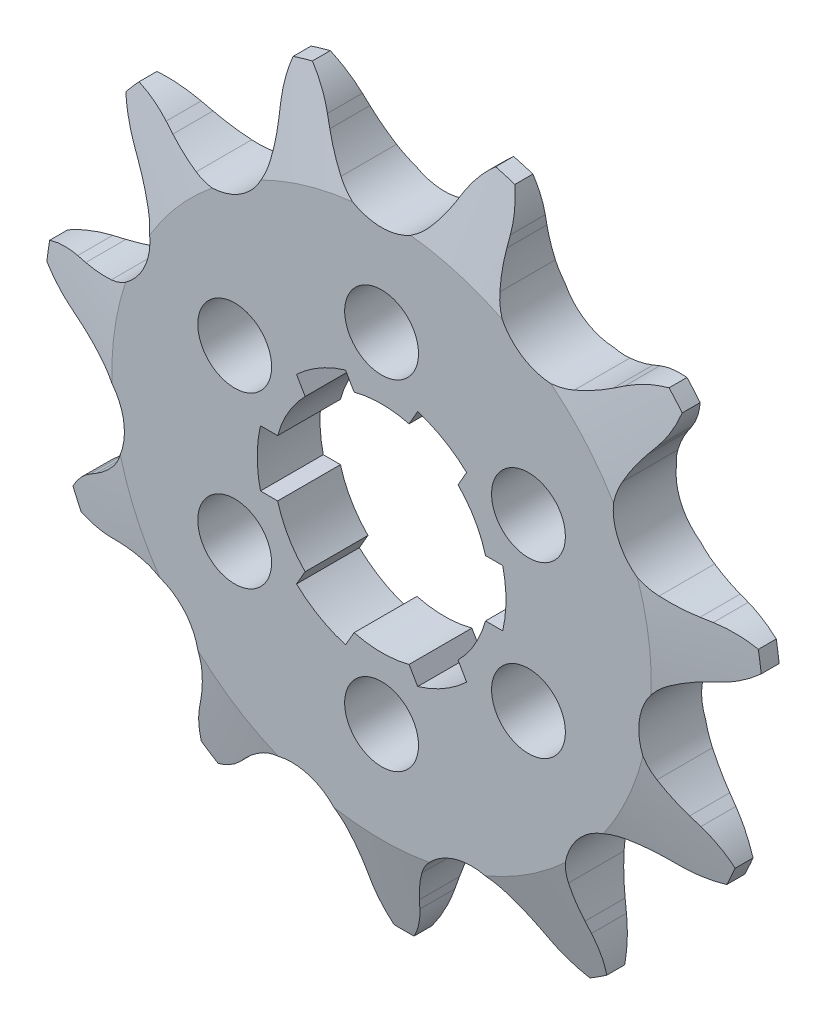
SolidWorks part; units mm, degrees
material "AISI 4130 Steel, annealed at 865C"
ref_plane "Front Plane" through (0, 0, 0) normal (0, 0, 1) x (1, 0, 0)
ref_plane "Top Plane" through (0, 0, 0) normal (0, 1, 0) x (1, 0, 0)
ref_plane "Right Plane" through (0, 0, 0) normal (1, 0, 0) x (0, 0, -1)
sketch "Sketch0" plane through (0, 0, 0) normal (0, 0, 1) x (1, 0, 0)
  line L0 (7.9375, -27.0326) -> (0, 0) construction
  line L1 (0, 0) -> (21.2924, -18.45) construction
  line L2 (0, 0) -> (-7.9375, -27.0326) construction
  line L3 (7.9375, -27.0326) -> (21.2924, -18.45) construction
  line L4 (7.9375, -27.0326) -> (-7.9375, -27.0326) construction
  line L5 (13.7041, -25.3103) -> (13.0504, -24.6313)
  line L6 (7.9375, -27.0326) -> (0, -29.3633) construction
  line L7 (2.1552, -28.7014) -> (2.338, -27.7767)
  line L8 (0, -27.0326) -> (0, -31.7951) construction
  line L9 (10.7525, -22.7279) -> (3.4891, -33.8353) construction
  line L10 (0, 0) -> (0, -27.0326) construction
  line L11 (13.0504, -24.6313) -> (3.4891, -33.8353) construction
  line L12 (0, -31.7951) -> (0, -32.9086) construction
  line L13 (19.9035, -19.3426) -> (13.7041, -25.3103) construction
  circle A0 centre (0, 0) radius 31.7951 construction
  circle A1 centre (0, 0) radius 28.1739 construction
  arc A2 (-8.2356, -35.414) -> (26.0745, -25.3397) centre (0, 0) ccw
  circle A3 centre (0, 0) radius 32.9086 construction
  circle A4 centre (7.9375, -27.0326) radius 5.08 construction
  arc A7 (10.7525, -22.7279) -> (3.242, -24.9331) centre (7.9375, -27.0326) ccw
  circle A8 centre (7.9375, -27.0326) radius 5.1435 construction
  arc A9 (13.7041, -25.3103) -> (26.0745, -25.3397) centre (19.9035, -19.3426) ccw
  arc A10 (13.0504, -24.6313) -> (10.7525, -22.7279) centre (3.4891, -33.8353) ccw
  arc A11 (2.1552, -28.7014) -> (-8.2356, -35.414) centre (-6.2865, -27.0326) cw
  arc A12 (2.338, -27.7767) -> (3.242, -24.9331) centre (15.3575, -30.3504) cw
  dimension "D1" = 5.1435
  dimension "R" = 5.1435
sketch "Sketch1" plane through (0, 0, 0) normal (1, 0, 0) x (0, 0, -1)
  line L0 (2.7781, 0) -> (-2.7781, 0)
  line L1 (-2.7781, 0) -> (-2.7781, 23.8576)
  line L2 (-2.7781, 23.8576) -> (-0.7937, 31.7951)
  line L3 (-0.7937, 31.7951) -> (0.7937, 31.7951)
  line L4 (0.7937, 31.7951) -> (2.7781, 23.8576)
  line L5 (2.7781, 23.8576) -> (2.7781, 0)
  line L7 (0, 31.7951) -> (0, 0) construction
  line L8 (-2.7781, 23.8576) -> (2.7781, 23.8576) construction
  line L9 (0, 31.7951) -> (0, -31.7951) construction
  line L10 (-2.7781, 23.8576) -> (-2.7781, 31.7951) construction
  line L11 (-2.7781, 31.7951) -> (-0.7937, 31.7951) construction
  line L12 (0.7937, 31.7951) -> (2.7781, 31.7951) construction
  line L13 (2.7781, 31.7951) -> (2.7781, 23.8576) construction
revolve "Revolve1" add sketch "Sketch1" angle 360 mid plane about L0
extrude "Cut-Extrude1" cut sketch "Sketch0" against normal through all and the other way through all
pattern_circular "CirPattern1" count 11 over 360 about axis through (0, 0, 0) along (0, 0, 1) of "Cut-Extrude1"
sketch "Sketch2" plane through (0, 0, 0) normal (0, 0, 1) x (1, 0, 0)
  circle A0 centre (0, 0) radius 7.9375 construction
  circle A1 centre (0, 0) radius 30.1625
  circle A2 centre (0, 0) radius 36.957 construction
  dimension "Bore" = 15.875
  dimension "Hub Dia." = 60.325
  dimension "OD" = 73.914
sketch "Sketch3" plane through (0, 0, 0) normal (0, 0, 1) x (1, 0, 0)
  circle A1 centre (0, 0) radius 8.5
  circle A2 centre (0, 0) radius 36.957 construction
  circle A3 centre (0, 0) radius 36.957
  dimension "D1" = 17
extrude "Cut-Extrude2" cut sketch "Sketch3" along normal through all and the other way through all flip side to cut
sketch "Sketch4" plane through (0, 0, -2.7781) normal (0, 0, -1) x (-1, 0, 0)
  line L0 (0, 0) -> (0, 15.875) construction
  circle A0 centre (0, 15.875) radius 3.175
  circle A1 centre (13.7482, 7.9375) radius 3.175
  circle A2 centre (13.7482, -7.9375) radius 3.175
  circle A3 centre (0, -15.875) radius 3.175
  circle A4 centre (-13.7482, -7.9375) radius 3.175
  circle A5 centre (-13.7482, 7.9375) radius 3.175
  point P17 (0, 0)
  dimension "D1" = 6
extrude "Cut-Extrude3" [suppressed] cut sketch "Sketch4" against normal through all
sketch "Sketch5" plane through (0, 0, 2.7781) normal (0, 0, 1) x (1, 0, 0)
  line L0 (0, 0) -> (8.5, 0) construction
  line L1 (8.5, 0) -> (11, 0) construction
  circle A0 centre (0, 0) radius 11 construction
  circle A1 centre (0, 0) radius 8.5 construction
sketch "Sketch6" plane through (0, 0, -2.7781) normal (0, 0, -1) x (-1, 0, 0)
  circle A0 centre (0, 0) radius 28.024 construction
  circle A1 centre (0, 0) radius 24.2521 construction
ref_plane "Plane1" [suppressed] through (-29.6833, 20.4889, 0) normal (-0.823, 0.5681, 0) x (0, 0, 1)
ref_plane "Plane2" [suppressed] through (-35.8049, 4.3475, 0) normal (-0.9927, 0.1205, 0) x (0, 0, 1)
ref_plane "Plane3" [suppressed] through (-33.724, -12.7898, 0) normal (-0.935, -0.3546, 0) x (0, 0, 1)
ref_plane "Plane4" [suppressed] through (-23.9174, -26.9972, 0) normal (-0.6631, -0.7485, 0) x (-0.7485, 0.6631, 0)
ref_plane "Plane5" [suppressed] through (-8.6316, -35.0198, 0) normal (-0.2393, -0.9709, 0) x (-0.9709, 0.2393, 0)
sketch "Sketch7" [suppressed] plane through (-29.6833, 20.4889, 0) normal (-0.823, 0.5681, 0) x (0, 0, 1)
  line L0 (-6.5106, 0) -> (7.7601, 0)
sketch "Sketch8" [suppressed] plane through (-35.8049, 4.3475, 0) normal (-0.9927, 0.1205, 0) x (0, 0, 1)
  line L0 (-7.786, 0) -> (10.2102, 0)
sketch "Sketch9" [suppressed] plane through (-33.724, -12.7898, 0) normal (-0.935, -0.3546, 0) x (0, 0, 1)
  line L0 (-7.6671, 0) -> (14.0341, 0)
  line L1 (-2.7781, 6.1399) -> (2.7781, 6.1399) construction
sketch "Sketch10" [suppressed] plane through (-23.9174, -26.9972, 0) normal (-0.6631, -0.7485, 0) x (-0.7485, 0.6631, 0)
  line L0 (0, -3.5829) -> (0, 5.4944)
sketch "Sketch11" [suppressed] plane through (-8.6316, -35.0198, 0) normal (-0.2393, -0.9709, 0) x (-0.9709, 0.2393, 0)
  line L0 (0, -5.4358) -> (0, 8.5188)
split line "Split Line7" [suppressed]
split line "Split Line8" [suppressed]
split line "Split Line9" [suppressed]
split line "Split Line10" [suppressed]
split line "Split Line11" [suppressed]
ref_plane "Motor Sprocket Middle Plane" through (0, 0, -0.0019) normal (0, 0, 1) x (1, 0, 0)
sketch "Sketch12" plane through (0, 0, -2.7781) normal (0, 0, -1) x (-1, 0, 0)
  line L0 (10.7121, 2.5) -> (8.6458, 2.5)
  line L1 (10.7121, -2.5) -> (8.6458, -2.5)
  line L2 (7.5211, -8.027) -> (6.488, -6.2375)
  line L3 (3.191, -10.527) -> (2.1578, -8.7375)
  line L4 (-3.191, -10.527) -> (-2.1578, -8.7375)
  line L5 (-7.5211, -8.027) -> (-6.488, -6.2375)
  line L6 (-10.7121, -2.5) -> (-8.6458, -2.5)
  line L7 (-10.7121, 2.5) -> (-8.6458, 2.5)
  line L8 (-7.5211, 8.027) -> (-6.488, 6.2375)
  line L9 (-3.191, 10.527) -> (-2.1578, 8.7375)
  line L10 (3.191, 10.527) -> (2.1578, 8.7375)
  line L11 (7.5211, 8.027) -> (6.488, 6.2375)
  arc A0 (2.1578, 8.7375) -> (-2.1578, 8.7375) centre (0, 0) ccw
  arc A1 (-3.191, 10.527) -> (-7.5211, 8.027) centre (0, 0) ccw
  arc A2 (-6.488, 6.2375) -> (-8.6458, 2.5) centre (0, 0) ccw
  arc A3 (-10.7121, 2.5) -> (-10.7121, -2.5) centre (0, 0) ccw
  arc A4 (-8.6458, -2.5) -> (-6.488, -6.2375) centre (0, 0) ccw
  arc A5 (-7.5211, -8.027) -> (-3.191, -10.527) centre (0, 0) ccw
  arc A6 (-2.1578, -8.7375) -> (2.1578, -8.7375) centre (0, 0) ccw
  arc A7 (3.191, -10.527) -> (7.5211, -8.027) centre (0, 0) ccw
  arc A8 (6.488, -6.2375) -> (8.6458, -2.5) centre (0, 0) ccw
  arc A9 (10.7121, -2.5) -> (10.7121, 2.5) centre (0, 0) ccw
  arc A10 (8.6458, 2.5) -> (6.488, 6.2375) centre (0, 0) ccw
  arc A11 (7.5211, 8.027) -> (3.191, 10.527) centre (0, 0) ccw
  point P30 (0, 0)
  dimension "D1" = 18
  dimension "D2" = 22
  dimension "D3" = 5
  dimension "D4" = 6
extrude "Cut-Extrude4" cut sketch "Sketch12" against normal through all
sketch "Sketch14" plane through (0, 0, 2.7781) normal (0, 0, 1) x (1, 0, 0)
  circle A0 centre (-12.9904, -7.5) radius 2.6
  circle A1 centre (0, 15) radius 2.6
  circle A2 centre (12.9904, -7.5) radius 2.6
  circle A3 centre (-12.9904, -7.5) radius 3
  circle A4 centre (0, 15) radius 3
  circle A5 centre (12.9904, -7.5) radius 3
  point P8 (0, 0)
  dimension "D1" = 5.2
  dimension "D4" = 20.7808
  dimension "D5" = 6
  dimension "D3" = 15
  dimension "D2" = 3
sketch "Sketch13" plane through (0, 0, -0.0019) normal (0, 0, 1) x (1, 0, 0)
  circle A0 centre (0, 0) radius 28.1739 construction
  circle A1 centre (0, 0) radius 20.6739
  circle A2 centre (0, 15) radius 4.7625
  circle A3 centre (0, 0) radius 11
  circle A4 centre (0, 0) radius 15 construction
  dimension "D1" = 7.5
  dimension "D2" = 9.525
sketch "Sketch15" plane through (0, 0, 2.7781) normal (0, 0, 1) x (1, 0, 0)
  circle A0 centre (0, 15) radius 3.2639
  circle A1 centre (12.9904, 7.5) radius 3.2639
  circle A2 centre (12.9904, -7.5) radius 3.2639
  circle A3 centre (0, -15) radius 3.2639
  circle A4 centre (-12.9904, -7.5) radius 3.2639
  circle A5 centre (-12.9904, 7.5) radius 3.2639
  point P15 (0, 0)
  dimension "D1" = 6.5278
  dimension "D2" = 6
extrude "Cut-Extrude5" cut sketch "Sketch15" against normal through all
sketch "Sketch16" plane through (0, 0, -0.0019) normal (0, 0, 1) x (1, 0, 0)
  circle A0 centre (0, 0) radius 9.525
  dimension "D1" = 19.05
extrude "Cut-Extrude6" cut sketch "Sketch16" against normal through all both and the other way through all
equation "\"360/N@Sketch0\" = 360/\"Teeth@CirPattern1\""
equation "\"Ds@Sketch0\" = 1.005 * \"Dr@Sketch0\" + 0.003"
equation "\"R@Sketch0\" = 1/2 * \"Ds@Sketch0\""
equation "\"A@Sketch0\" = 35 +  ( 60 / \"Teeth@CirPattern1\" ) "
equation "\"B@Sketch0\" = 18 -  ( 56 / \"Teeth@CirPattern1\" )"
equation "\"ac@Sketch0\" = 0.8 * \"Dr@Sketch0\""
equation "\"ab@Sketch0\" = 1.4 * \"Dr@Sketch0\""
equation "\"J@Sketch0\" = 0.3 * \"Pitch@Sketch0\""
equation "\"h@Sketch1\" = \"Pitch@Sketch0\" / 2"
equation "\"g@Sketch1\" = \"h@Sketch1\" / 4"
